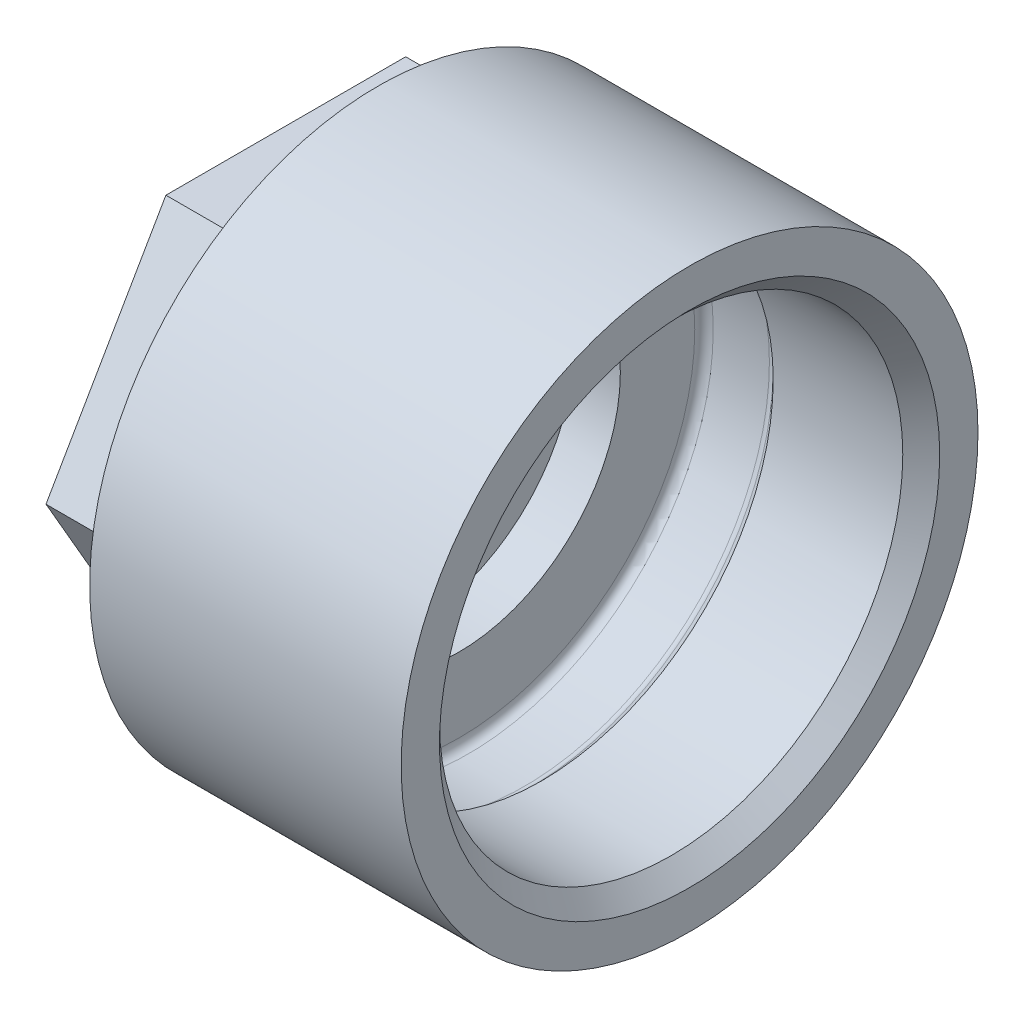
SolidWorks part; units mm, degrees
material "Простая углеродистая сталь"
ref_plane "Спереди" through (0, 0, 0) normal (0, 0, 1) x (1, 0, 0)
ref_plane "Сверху" through (0, 0, 0) normal (0, 1, 0) x (1, 0, 0)
ref_plane "Справа" through (0, 0, 0) normal (1, 0, 0) x (0, 0, -1)
sketch "Эскиз1" plane through (0, 0, 0) normal (0, 0, 1) x (1, 0, 0)
  line L0 (0, 0) -> (-76.819, 0) construction
  line L1 (0, 21.68) -> (0, 25)
  line L2 (0, 25) -> (-27, 25)
  line L3 (-27, 25) -> (-27, 21)
  line L4 (-27, 21) -> (-35, 21)
  line L5 (-35, 21) -> (-35, 2)
  line L6 (-35, 2) -> (-24, 2)
  line L7 (-24, 2) -> (-24, 14)
  line L8 (-24, 14) -> (-20, 14)
  line L9 (-20, 14) -> (-20, 20.45)
  line L10 (-19.2, 21.25) -> (-14.3314, 21.25)
  line L11 (-13.7657, 21.0157) -> (-12.83, 20.08)
  line L12 (-12.83, 20.08) -> (-1.6, 20.08)
  line L13 (-1.6, 20.08) -> (0, 21.68)
  arc A0 (-20, 20.45) -> (-19.2, 21.25) centre (-19.2, 20.45) cw
  arc A1 (-14.3314, 21.25) -> (-13.7657, 21.0157) centre (-14.3314, 20.45) cw
  point P16 (-20, 21.25)
  point P19 (-14, 21.25)
  dimension "D12" = 0.8
  dimension "D1" = 4
  dimension "D2" = 28
  dimension "D3" = 42.5
  dimension "D4" = 45
  dimension "D5" = 42
  dimension "D6" = 50
  dimension "D7" = 8
  dimension "D8" = 20
  dimension "D9" = 24
  dimension "D10" = 35
  dimension "D11" = 6
  dimension "D13" = 1.6
  dimension "D14" = 40.16
revolve "Повернуть1" add sketch "Эскиз1" angle 360 about L0
cosmetic thread "Условное изображение резьбы1" parameters "D2"=42
sketch "Эскиз4" plane through (-35, 0, 0) normal (-1, 0, 0) x (0, 0, 1)
  line L1 (20.7846, 0) -> (10.3923, 18)
  line L2 (10.3923, 18) -> (-10.3923, 18)
  line L3 (-10.3923, 18) -> (-20.7846, 0)
  line L4 (-20.7846, 0) -> (-10.3923, -18)
  line L5 (-10.3923, -18) -> (10.3923, -18)
  line L6 (10.3923, -18) -> (20.7846, 0)
  circle A0 centre (0, 0) radius 18 construction
  dimension "D1" = 36
extrude "Вырез-Вытянуть1" cut sketch "Эскиз4" against normal blind 7 flip side to cut
